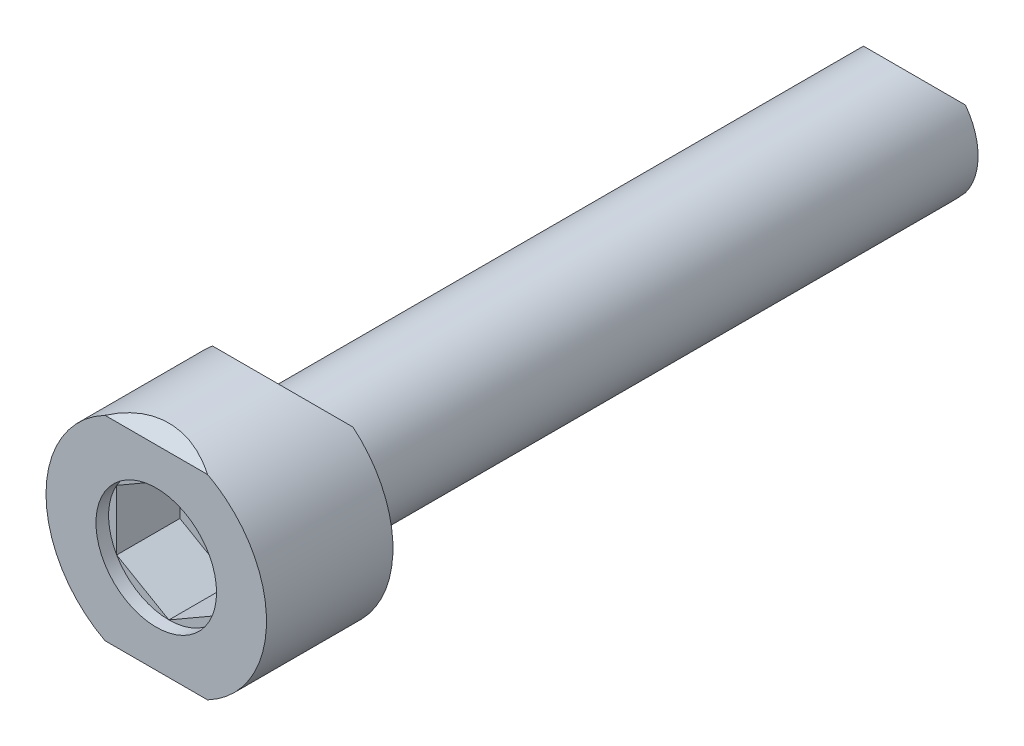
SolidWorks part; units mm, degrees
ref_plane "Front Plane" through (0, 0, 0) normal (0, 0, 1) x (1, 0, 0)
ref_plane "Top Plane" through (0, 0, 0) normal (0, 1, 0) x (1, 0, 0)
ref_plane "Right Plane" through (0, 0, 0) normal (1, 0, 0) x (0, 0, -1)
sketch "Sketch1" plane through (0, 0, 0) normal (1, 0, 0) x (0, 0, -1)
  line L0 (-21.3768, 0) -> (27.2645, 0) construction
  line L1 (11.5, -2.5) -> (-12.5, -2.5)
  line L2 (12.5, -1.5) -> (12.5, 1.5)
  line L3 (11.5, 2.5) -> (-12.5, 2.5)
  line L5 (12.5, -2.5) -> (-12.5, 2.5) construction
  line L6 (12.5, 2.5) -> (-12.5, -2.5) construction
  line L7 (12.5, 1.5) -> (11.5, 2.5)
  line L8 (-13.5, -4.36) -> (-17, -4.36)
  line L9 (-12.5, -3.36) -> (-12.5, -2.5)
  line L10 (-13.5, 4.36) -> (-17, 4.36)
  line L11 (-17.5, -3.86) -> (-17.5, 3.86)
  line L12 (-12.5, -4.36) -> (-17.5, 4.36) construction
  line L13 (-12.5, 4.36) -> (-17.5, -4.36) construction
  line L14 (12.5, -1.5) -> (11.5, -2.5)
  line L15 (-12.5, -3.36) -> (-13.5, -4.36)
  line L16 (-12.5, 3.36) -> (-13.5, 4.36)
  line L17 (-17, 4.36) -> (-17.5, 3.86)
  line L18 (-17, -4.36) -> (-17.5, -3.86)
  line L19 (-12.5, 2.5) -> (-12.5, 3.36)
  point P0 (0, 0)
  point P8 (-15, 0)
  dimension "D1" = 25
  dimension "D2" = 5
  dimension "D3" = 8.72
  dimension "D4" = 5
extrude "Boss-Extrude1" add sketch "Sketch1" along normal blind 10
sketch "Sketch2" plane through (0, 0, 17.5) normal (0, 0, 1) x (1, 0, 0)
  line L0 (0, -3.86) -> (0, -4.36) construction
  circle A0 centre (4.36, 0) radius 4.36
  dimension "D1" = 8.72
  dimension "D2" = 4.36
extrude "Cut-Extrude4" cut sketch "Sketch2" against normal through all flip side to cut contours A0
sketch "Sketch3" plane through (0, 0, 17.5) normal (0, 0, 1) x (1, 0, 0)
  circle A0 centre (4.36, 0) radius 2.3843
  arc A2 (2.3327, 3.86) -> (2.3327, -3.86) centre (4.36, 0) ccw construction
extrude "Cut-Extrude7" cut sketch "Sketch3" against normal blind 0.5
sketch "Sketch4" plane through (0, 0, 17) normal (0, 0, 1) x (1, 0, 0)
  line L1 (4.36, 2.3843) -> (2.2951, 1.1922)
  line L2 (2.2951, 1.1922) -> (2.2951, -1.1922)
  line L3 (2.2951, -1.1922) -> (4.36, -2.3843)
  line L4 (4.36, -2.3843) -> (6.4249, -1.1922)
  line L5 (6.4249, -1.1922) -> (6.4249, 1.1922)
  line L6 (6.4249, 1.1922) -> (4.36, 2.3843)
  circle A0 centre (4.36, 0) radius 2.0649 construction
extrude "Cut-Extrude8" cut sketch "Sketch4" against normal blind 2.5
sketch "Sketch5" plane through (0, 0, -12.5) normal (0, 0, -1) x (-1, 0, 0)
  circle A0 centre (-4.36, 0) radius 2.5
  arc A1 (-8.4538, 1.5) -> (-8.4538, -1.5) centre (-4.36, 0) ccw construction
  dimension "D1" = 5
extrude "Cut-Extrude9" cut sketch "Sketch5" against normal blind 25 flip side to cut contours A0
